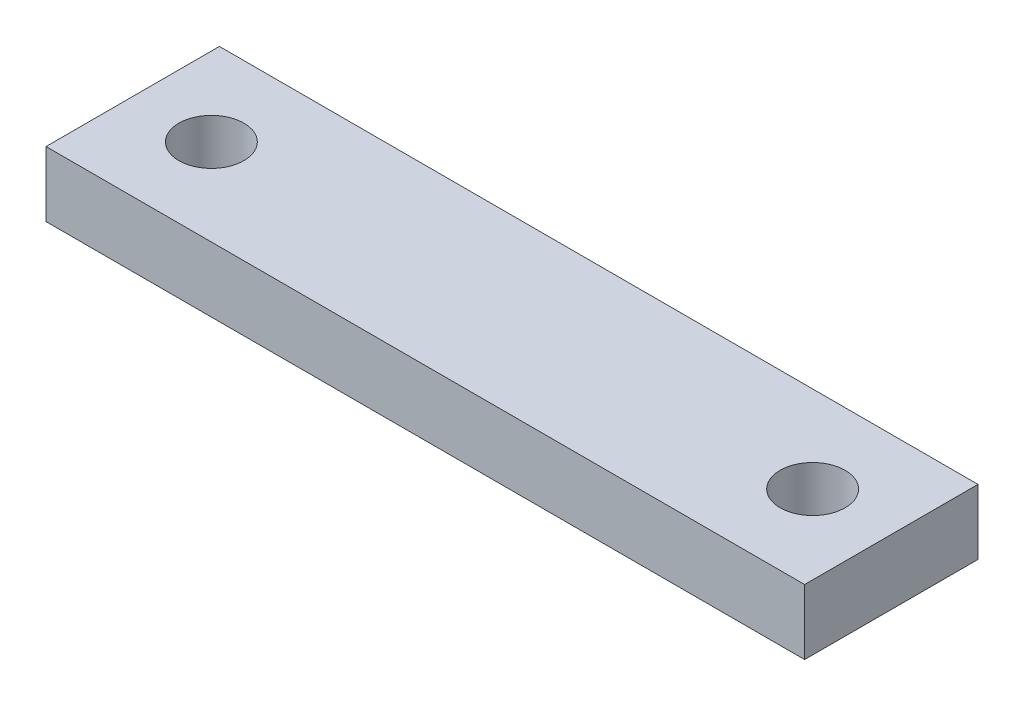
SolidWorks part; units mm, degrees
ref_plane "Front Plane" through (0, 0, 0) normal (0, 0, 1) x (1, 0, 0)
ref_plane "Top Plane" through (0, 0, 0) normal (0, 1, 0) x (1, 0, 0)
ref_plane "Right Plane" through (0, 0, 0) normal (1, 0, 0) x (0, 0, -1)
sketch "Sketch1" plane through (0, 0, 0) normal (0, 1, 0) x (1, 0, 0)
  line L0 (0, 17.8775) -> (0, -13.3862) construction
  line L1 (-17.5, -4) -> (17.5, -4)
  line L2 (-17.5, -4) -> (-17.5, 4)
  line L3 (-17.5, 4) -> (17.5, 4)
  line L4 (17.5, -4) -> (17.5, 4)
  line L5 (-17.5, -4) -> (17.5, 4) construction
  line L6 (-17.5, 4) -> (17.5, -4) construction
  circle A0 centre (-13.87, 0) radius 1.5
  circle A1 centre (13.87, 0) radius 1.5
  point P0 (0, 0)
  dimension "D4" = 3
  dimension "D1" = 35
  dimension "D2" = 8
  dimension "D3" = 13.87
extrude "Boss-Extrude1" add sketch "Sketch1" along normal blind 3
